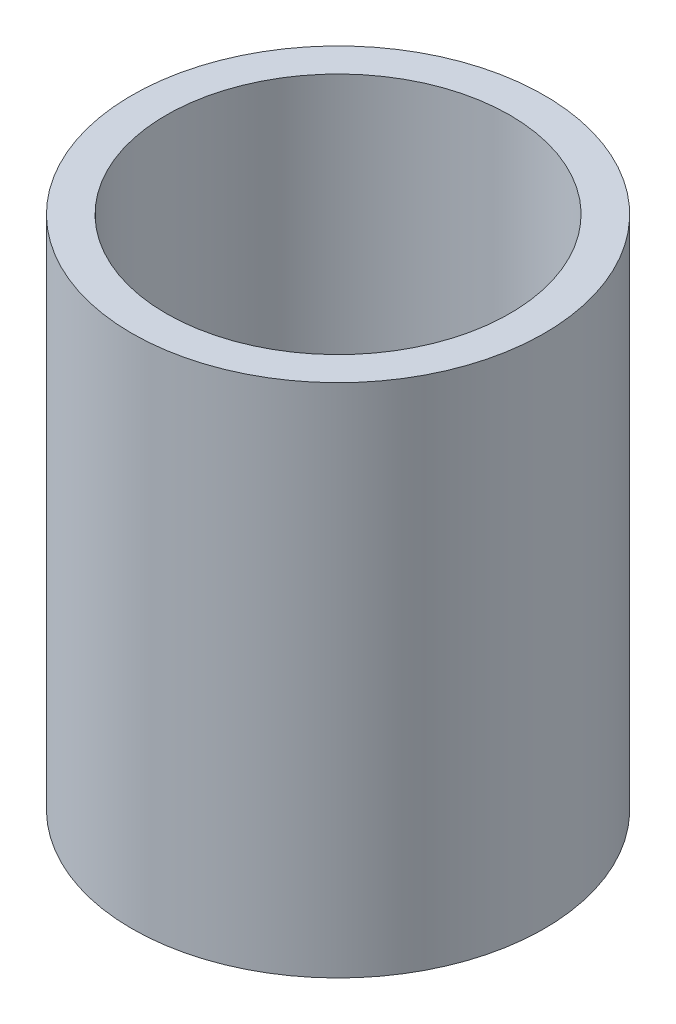
SolidWorks part; units mm, degrees
ref_plane "Front Plane" through (0, 0, 0) normal (0, 0, 1) x (1, 0, 0)
ref_plane "Top Plane" through (0, 0, 0) normal (0, 1, 0) x (1, 0, 0)
ref_plane "Right Plane" through (0, 0, 0) normal (1, 0, 0) x (0, 0, -1)
sketch "Sketch1" plane through (0, 0, 0) normal (0, 1, 0) x (1, 0, 0)
  circle A0 centre (0, 0) radius 60
  dimension "D1" = 120
extrude "Boss-Extrude1" add sketch "Sketch1" along normal blind 150
sketch "Sketch2" plane through (0, 150, 0) normal (0, 1, 0) x (1, 0, 0)
  circle A0 centre (0, 0) radius 50
  dimension "D1" = 100
extrude "Cut-Extrude1" cut sketch "Sketch2" against normal blind 130
